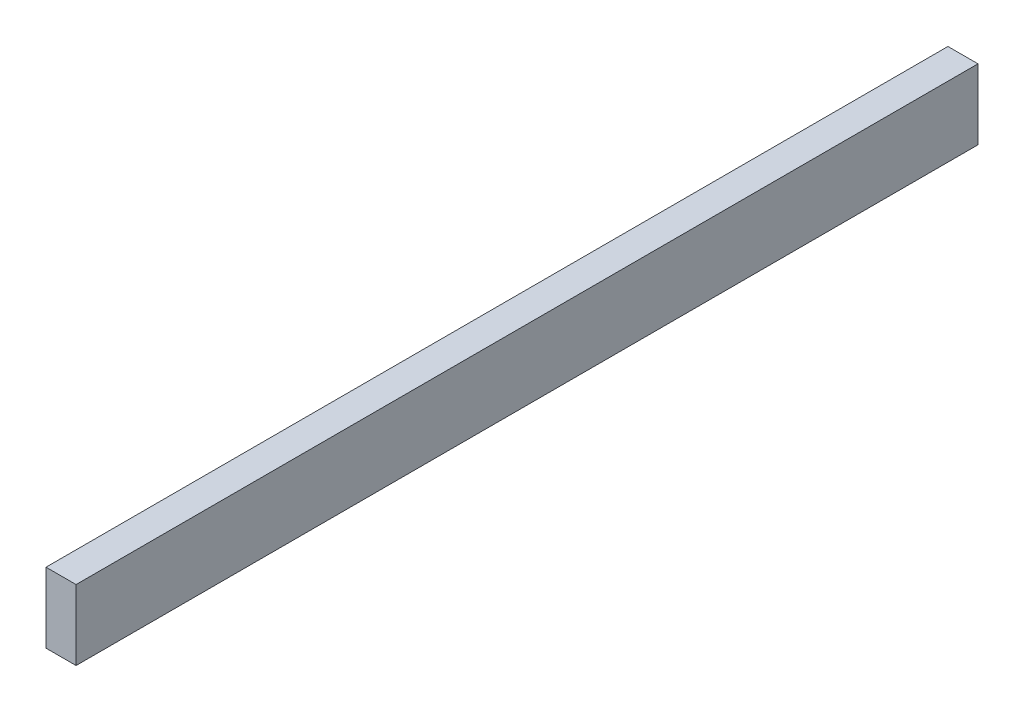
SolidWorks part; units mm, degrees
ref_plane "Front" through (0, 0, 0) normal (0, 0, 1) x (1, 0, 0)
ref_plane "Top" through (0, 0, 0) normal (0, 1, 0) x (1, 0, 0)
ref_plane "Right" through (0, 0, 0) normal (1, 0, 0) x (0, 0, -1)
sketch "Sketch1" plane through (0, 0, 0) normal (0, 0, 1) x (1, 0, 0)
  line L0 (-19.05, 44.45) -> (19.05, -44.45) construction
  line L1 (-19.05, 44.45) -> (19.05, 44.45)
  line L2 (-19.05, 44.45) -> (-19.05, -44.45)
  line L3 (-19.05, -44.45) -> (19.05, -44.45)
  line L4 (19.05, 44.45) -> (19.05, -44.45)
  dimension "D1" = 38.1
  dimension "D2" = 88.9
extrude "Extrude1" add sketch "Sketch1" along normal mid plane 1143
sketch "Sketch2" plane through (0, 44.45, 0) normal (0, 1, 0) x (1, 0, 0)
  line L0 (19.05, 571.5) -> (-19.05, 533.4)
  line L1 (-19.05, -571.5) -> (-19.05, 571.5) construction
  line L2 (19.05, 571.5) -> (-19.05, 571.5) construction
  line L3 (19.05, 571.5) -> (-19.05, 571.5)
  line L4 (-19.05, 571.5) -> (-19.05, 533.4)
  dimension "D1" = 45
extrude "Cut-Extrude1" [suppressed] cut sketch "Sketch2" against normal through all
mirror "Mirror1" [suppressed] about plane through (0, 0, 0) normal (0, 0, 1)
